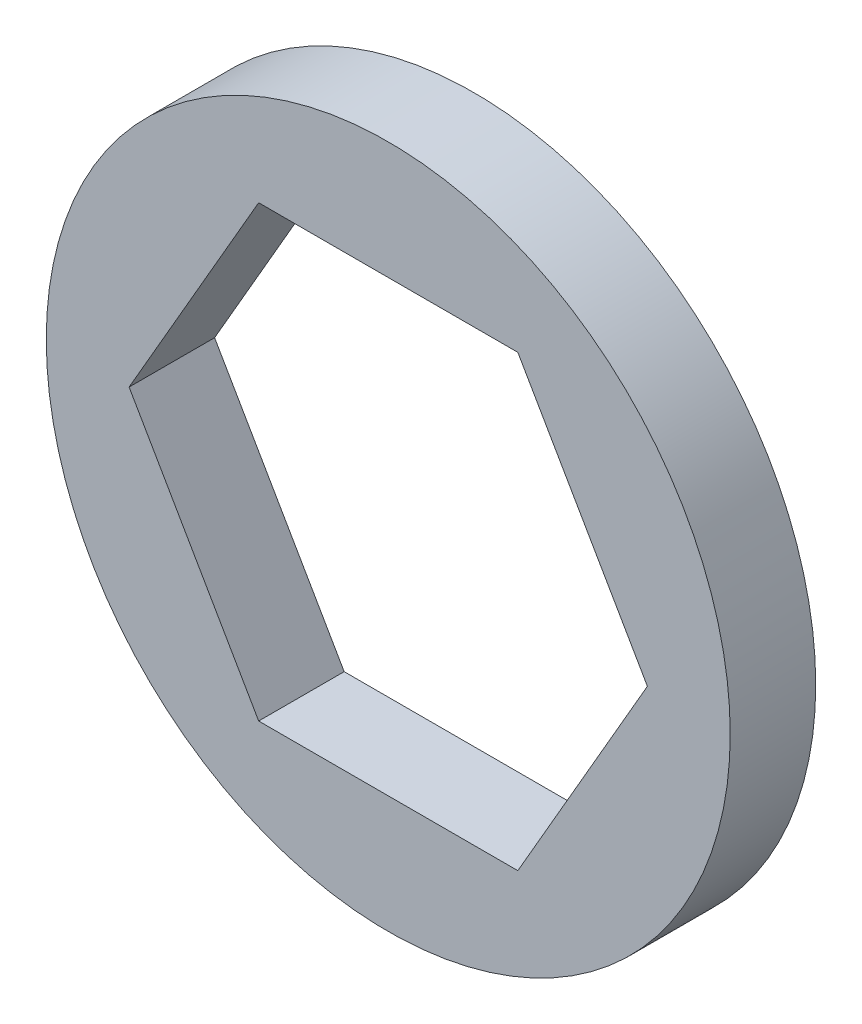
SolidWorks part; units mm, degrees
material "ABS"
ref_plane "Front Plane" through (0, 0, 0) normal (0, 0, 1) x (1, 0, 0)
ref_plane "Top Plane" through (0, 0, 0) normal (0, 1, 0) x (1, 0, 0)
ref_plane "Right Plane" through (0, 0, 0) normal (1, 0, 0) x (0, 0, -1)
sketch "Sketch1" plane through (0, 0, 0) normal (0, 0, 1) x (1, 0, 0)
  line L1 (3.0311, 0) -> (1.5155, 2.625)
  line L2 (1.5155, 2.625) -> (-1.5155, 2.625)
  line L3 (-1.5155, 2.625) -> (-3.0311, 0)
  line L4 (-3.0311, 0) -> (-1.5155, -2.625)
  line L5 (-1.5155, -2.625) -> (1.5155, -2.625)
  line L6 (1.5155, -2.625) -> (3.0311, 0)
  circle A0 centre (0, 0) radius 2.625 construction
  circle A1 centre (0, 0) radius 4
  dimension "D1" = 5.25
  dimension "D2" = 8
extrude "Boss-Extrude1" add sketch "Sketch1" along normal blind 1
